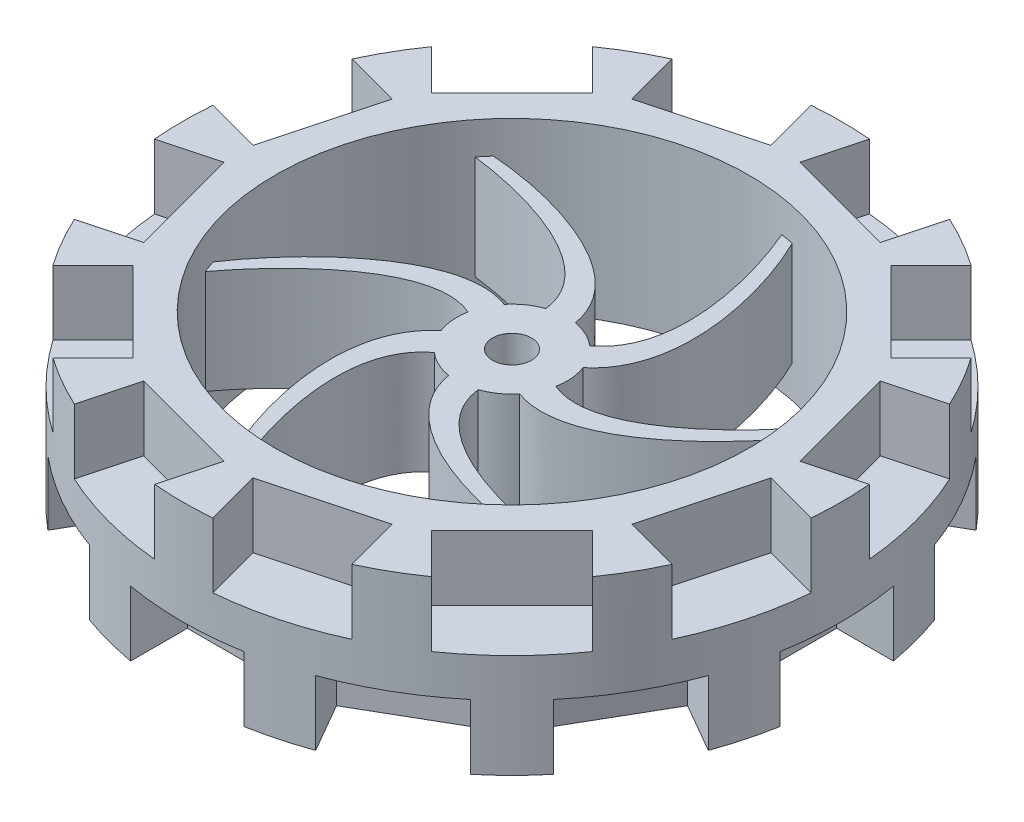
SolidWorks part; units mm, degrees
ref_plane "Front Plane" through (0, 0, 0) normal (0, 0, 1) x (1, 0, 0)
ref_plane "Top Plane" through (0, 0, 0) normal (0, 1, 0) x (1, 0, 0)
ref_plane "Right Plane" through (0, 0, 0) normal (1, 0, 0) x (0, 0, -1)
sketch "Sketch1" plane through (0, 0, 0) normal (0, 1, 0) x (1, 0, 0)
  circle A0 centre (0, 0) radius 50.8
  dimension "D1" = 101.6
extrude "Boss-Extrude1" add sketch "Sketch1" along normal mid plane 26
sketch "Sketch2" plane through (0, -13, 0) normal (0, -1, 0) x (1, 0, 0)
  circle A0 centre (0, 0) radius 3
  dimension "D1" = 6
extrude "Cut-Extrude1" cut sketch "Sketch2" against normal through all contours A0
sketch "Sketch4" plane through (0, -13, 0) normal (0, -1, 0) x (1, 0, 0)
  line L0 (0, 0) -> (0, 49.3) construction
  line L1 (-8.75, 49.3) -> (8.75, 49.3)
  line L3 (8.75, 41.3) -> (-8.75, 41.3)
  line L4 (-8.75, 49.3) -> (-8.75, 41.3)
  line L6 (8.75, 49.3) -> (8.75, 41.3)
  line L8 (-8.75, 49.3) -> (-8.75, 53.3)
  line L9 (-8.75, 53.3) -> (8.75, 53.3)
  line L10 (8.75, 53.3) -> (8.75, 49.3)
  circle A0 centre (0, 0) radius 49.3
  point P9 (0, 41.3)
  dimension "D1" = 8
  dimension "D2" = 98.6
  dimension "D3" = 17.5
  dimension "D4" = 4
extrude "Cut-Extrude2" cut sketch "Sketch4" against normal blind 10
sketch "Sketch6" plane through (0, 13, 0) normal (0, 1, 0) x (1, 0, 0)
  line L0 (0, 0) -> (-13.148, -49.069) construction
  line L1 (0, 0) -> (0, -50.8) construction
  line L2 (-4.6962, -51.3337) -> (-21.5999, -46.8044)
  line L3 (-21.5999, -46.8044) -> (-19.1411, -37.6281)
  line L4 (-19.1411, -37.6281) -> (-2.2374, -42.1574)
  line L5 (-4.6962, -51.3337) -> (-2.2374, -42.1574)
  circle A0 centre (0, 0) radius 50.8 construction
  point P10 (-10.6892, -39.8927)
  dimension "D1" = 15
  dimension "D2" = 9.5
  dimension "D3" = 17.5
extrude "Cut-Extrude3" cut sketch "Sketch6" against normal blind 10
pattern_circular "CirPattern1" count 12 every 30 about axis through (0, 0, 0) along (0, 1, 0) of "Cut-Extrude2", "Cut-Extrude3"
sketch "Sketch8" plane through (0, 13, 0) normal (0, 1, 0) x (1, 0, 0)
  circle A0 centre (0, 0) radius 36.5
  dimension "D1" = 73
extrude "Cut-Extrude4" cut sketch "Sketch8" against normal blind 5
mirror "Mirror1" about plane through (0, 0, 0) normal (0, 1, 0) of "Cut-Extrude4"
ref_plane "Plane1" through (0, 11, 0) normal (0, 1, 0) x (1, 0, 0)
ref_plane "Plane2" through (0, -11, 0) normal (0, 1, 0) x (1, 0, 0)
sketch "Sketch11" plane through (0, -8, 0) normal (0, -1, 0) x (1, 0, 0)
  circle A0 centre (0, 0) radius 12.1667
  circle A1 centre (0, 0) radius 24.3333
  circle A2 centre (0, 0) radius 36.5
  circle A3 centre (0, 0) radius 8.5
  spline S0 degree 3 poles (-1.3758, 8.3879) (-1.1429, 9.7457) (2.6661, 19.8579) (19.0893, 23.8359) (27.2055, 24.3333) knots 0.183853 0.183853 0.183853 0.183853 0.285381 1 1 1 1
  spline S1 degree 3 poles (28.4975, 22.8067) (21.5478, 22.0041) (6.0313, 18.3561) (2.9555, 9.2755) (2.8161, 8.0199) knots 0 0 0 0 0.70456 0.80787 0.80787 0.80787 0.80787
  spline S2 degree 3 poles (33.9999, -13.2762) (29.83, -7.6588) (18.9125, 3.9548) (9.5106, 2.0783) (8.3535, 1.5711) knots 0 0 0 0 0.70456 0.80787 0.80787 0.80787 0.80787
  spline S3 degree 3 poles (6.5762, 5.3854) (7.8686, 5.8626) (18.5305, 7.62) (30.1872, -4.6139) (34.676, -11.394) knots 0.183853 0.183853 0.183853 0.183853 0.285381 1 1 1 1
  spline S4 degree 3 poles (5.5024, -36.0829) (8.2822, -29.663) (12.8812, -14.4013) (6.5551, -7.1973) (5.5374, -6.4488) knots 0 0 0 0 0.70456 0.80787 0.80787 0.80787 0.80787
  spline S5 degree 3 poles (7.9521, -3.0025) (9.0115, -3.8831) (15.8644, -12.2379) (11.0979, -28.4498) (7.4705, -35.7273) knots 0.183853 0.183853 0.183853 0.183853 0.285381 1 1 1 1
  spline S6 degree 3 poles (-28.4975, -22.8067) (-21.5478, -22.0041) (-6.0313, -18.3561) (-2.9555, -9.2755) (-2.8161, -8.0199) knots 0 0 0 0 0.70456 0.80787 0.80787 0.80787 0.80787
  spline S7 degree 3 poles (1.3758, -8.3879) (1.1429, -9.7457) (-2.6661, -19.8579) (-19.0893, -23.8359) (-27.2055, -24.3333) knots 0.183853 0.183853 0.183853 0.183853 0.285381 1 1 1 1
  spline S8 degree 3 poles (-33.9999, 13.2762) (-29.83, 7.6588) (-18.9125, -3.9548) (-9.5106, -2.0783) (-8.3535, -1.5711) knots 0 0 0 0 0.70456 0.80787 0.80787 0.80787 0.80787
  spline S9 degree 3 poles (-6.5762, -5.3854) (-7.8686, -5.8626) (-18.5305, -7.62) (-30.1872, 4.6139) (-34.676, 11.394) knots 0.183853 0.183853 0.183853 0.183853 0.285381 1 1 1 1
  spline S10 degree 3 poles (-5.5024, 36.0829) (-8.2822, 29.663) (-12.8812, 14.4013) (-6.5551, 7.1973) (-5.5374, 6.4488) knots 0 0 0 0 0.70456 0.80787 0.80787 0.80787 0.80787
  spline S11 degree 3 poles (-7.9521, 3.0025) (-9.0115, 3.8831) (-15.8644, 12.2379) (-11.0979, 28.4498) (-7.4705, 35.7273) knots 0.183853 0.183853 0.183853 0.183853 0.285381 1 1 1 1
  point P56 (0, 0)
  circle M1 centre (0, 0) radius 36.5
  dimension "D1" = 48.6667
  dimension "D2" = 24.3333
  dimension "D3" = 73
  dimension "D8" = 17
  dimension "D5" = 4
  dimension "D6" = 3
  dimension "D7" = 2
extrude "Cut-Extrude5" cut sketch "Sketch11" against normal through all contours A1 S11 S8 M1 | A0 S11 A1 S8 | A3 S11 A0 S8 | A0 S10 A3 S0 | A1 S10 A0 S0 | S10 A1 S0 M1 | A0 S3 A1 S1 | A3 S3 A0 S1 | A1 S3 S1 M1 | A0 S5 A1 S2 | A3 S5 A0 S2 | A1 S5 S2 M1 | A1 S7 S4 M1 | A0 S7 A1 S4 | A3 S7 A0 S4 | A0 S9 A1 S6 | A3 S9 A0 S6 | A1 S9 S6 M1
